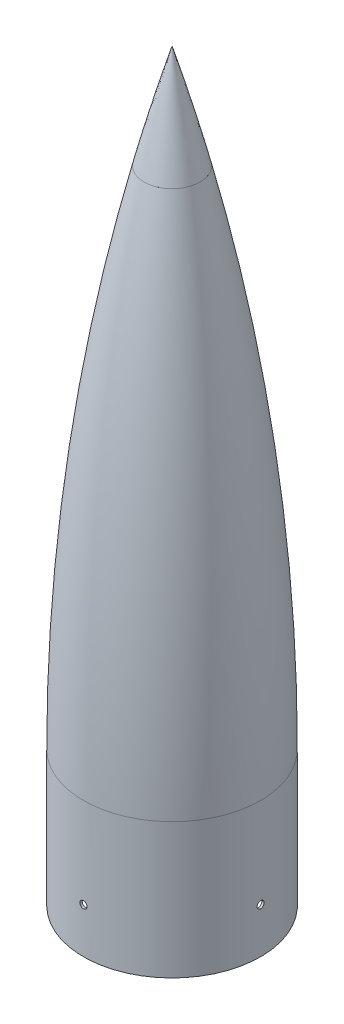
SolidWorks part; units mm, degrees
ref_plane "Front Plane" through (0, 0, 0) normal (0, 0, 1) x (1, 0, 0)
ref_plane "Top Plane" through (0, 0, 0) normal (0, 1, 0) x (1, 0, 0)
ref_plane "Right Plane" through (0, 0, 0) normal (1, 0, 0) x (0, 0, -1)
sketch "Sketch1" plane through (0, 0, 0) normal (0, 0, 1) x (1, 0, 0)
  line L0 (0, 0) -> (0, 419.1) construction
  line L1 (-49.8856, 0) -> (-48.6156, 0)
  line L2 (-49.8856, 0) -> (-49.8856, 76.2)
  line L4 (-48.6156, 0) -> (-48.6156, 76.2)
  line L5 (-14.4713, 360.68) -> (0, 360.68)
  line L6 (0, 419.1) -> (0, 360.68)
  line L7 (-14.4713, 360.68) -> (-15.7784, 360.68)
  arc A0 (-49.8856, 76.2) -> (0, 419.1) centre (1153.5577, 76.2) cw
  arc A1 (-48.6156, 76.2) -> (-14.4713, 360.68) centre (1153.5577, 76.2) cw
  dimension "D1" = 1.27
  dimension "D2" = 76.2
  dimension "D3" = 49.8856
  dimension "D4" = 419.1
  dimension "D5" = 58.42
ref_plane "Plane1" through (0, 457.2, 0) normal (0, 1, 0) x (1, 0, 0)
revolve "Revolve4" add sketch "Sketch1" angle 360 about L0
sketch "Sketch4" plane through (0, 0, 0) normal (0, 0, 1) x (1, 0, 0)
  line L0 (0, 419.1) -> (0, 360.68) construction
  line L1 (0, 419.1) -> (0, 360.68)
  line L3 (15.7784, 360.68) -> (-15.7784, 360.68) construction
  line L7 (15.7784, 360.68) -> (-15.7784, 360.68)
  line L8 (0, 360.68) -> (0, 393.4786) construction
  arc A0 (0, 419.1) -> (-49.8856, 76.2) centre (1153.5577, 76.2) ccw construction
  arc A1 (0, 419.1) -> (-49.8856, 76.2) centre (1153.5577, 76.2) ccw
revolve "Revolve5" add sketch "Sketch4" angle 360 about L8
extrude "Cut-Extrude1" cut sketch "Sketch5" against normal blind 12.7
sketch "Sketch5" plane through (-80.2742, -85.9656, 50.8) normal (0, 0, 1) x (1, 0, 0)
  circle A0 centre (80.2742, 111.3656) radius 1.9844
pattern_circular "CirPattern1" count 4 over 360 about axis through (0, 0, 0) along (0, -1, 0) of "Cut-Extrude1"
